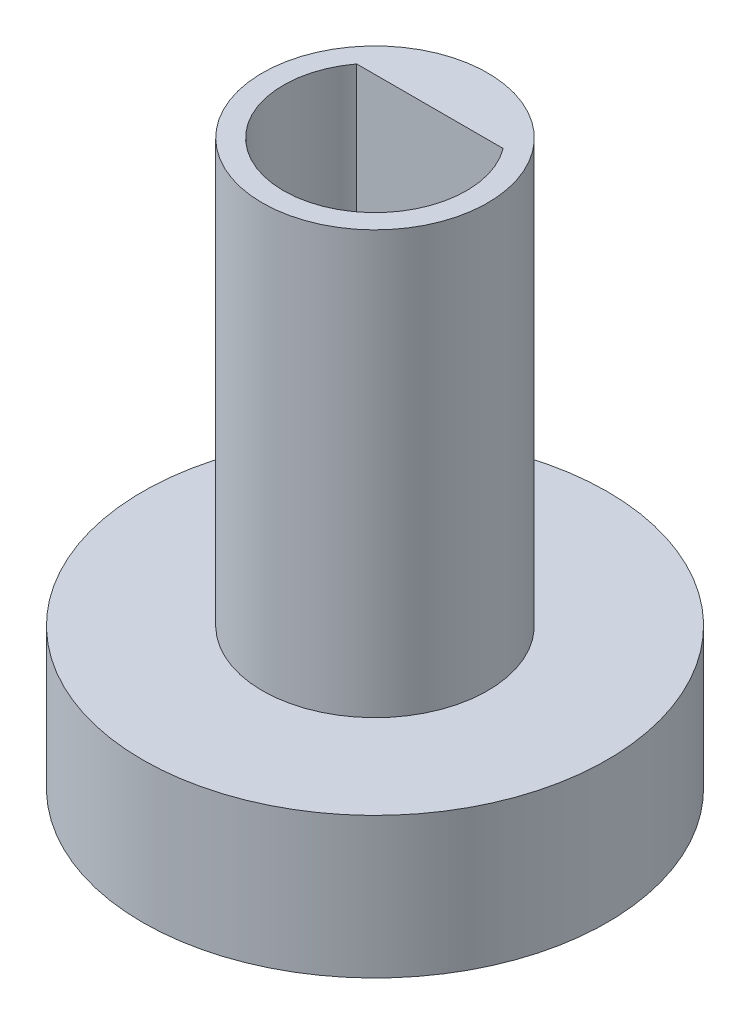
SolidWorks part; units mm, degrees
ref_plane "Alzado" through (0, 0, 0) normal (0, 0, 1) x (1, 0, 0)
ref_plane "Planta" through (0, 0, 0) normal (0, 1, 0) x (1, 0, 0)
ref_plane "Vista lateral" through (0, 0, 0) normal (1, 0, 0) x (0, 0, -1)
sketch "Croquis1" plane through (0, 0, 0) normal (0, 1, 0) x (1, 0, 0)
  line L0 (-2.6, 1.95) -> (2.6, 1.95)
  line L1 (-2.6, -3.25) -> (2.6, -3.25) construction
  circle A0 centre (0, 0) radius 3.25 construction
  arc A1 (-2.6, 1.95) -> (2.6, 1.95) centre (0, 0) ccw
  circle A2 centre (0, 0) radius 8.25
  dimension "D1" = 6.5
  dimension "D3" = 16.5
  dimension "D2" = 5.2
extrude "Saliente-Extruir1" add sketch "Croquis1" along normal blind 5
sketch "Croquis2" plane through (0, 5, 0) normal (0, 1, 0) x (1, 0, 0)
  line L0 (2.6, 1.95) -> (-2.6, 1.95) construction
  line L1 (2.6, 1.95) -> (-2.6, 1.95)
  circle A0 centre (0, 0) radius 4
  arc A1 (-2.6, 1.95) -> (2.6, 1.95) centre (0, 0) ccw construction
  arc A2 (-2.6, 1.95) -> (2.6, 1.95) centre (0, 0) ccw
  dimension "D1" = 8
extrude "Saliente-Extruir2" add sketch "Croquis2" along normal blind 15
